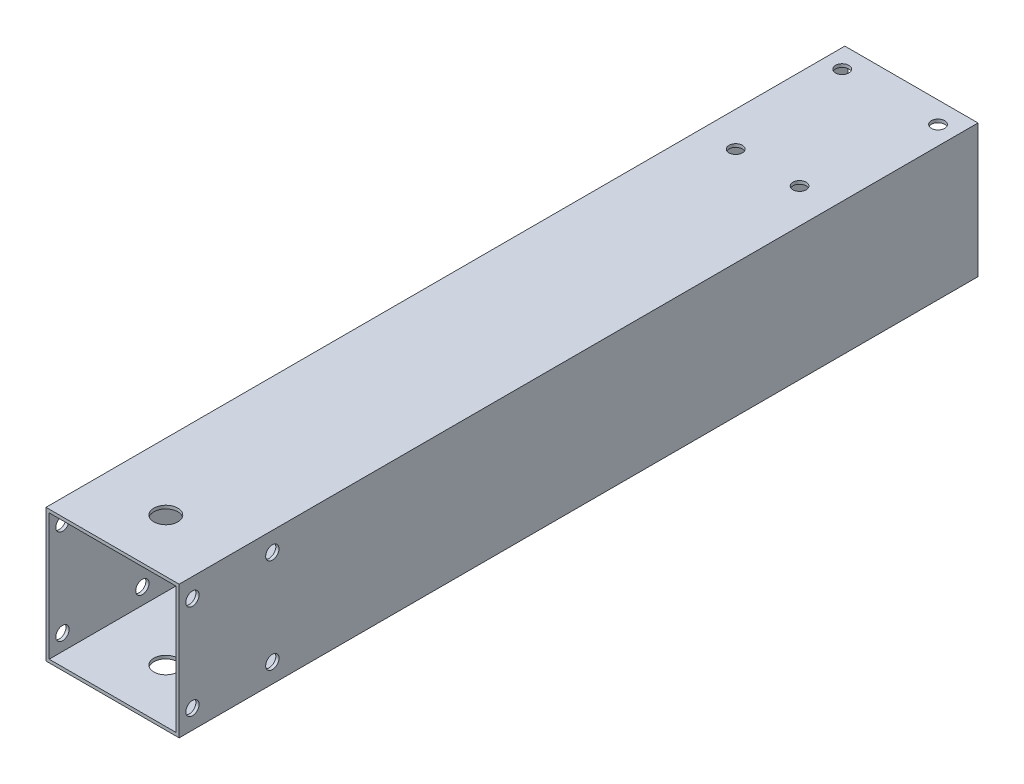
SolidWorks part; units mm, degrees
ref_plane "Alzado" through (0, 0, 0) normal (0, 0, 1) x (1, 0, 0)
ref_plane "Planta" through (0, 0, 0) normal (0, 1, 0) x (1, 0, 0)
ref_plane "Vista lateral" through (0, 0, 0) normal (1, 0, 0) x (0, 0, -1)
sketch "Croquis1" plane through (0, 0, 0) normal (0, 0, 1) x (1, 0, 0)
  line L0 (-23.8, 23.8) -> (-23.8, -23.8)
  line L1 (-25, 25) -> (25, 25)
  line L2 (-25, 25) -> (-25, -25)
  line L3 (-25, -25) -> (25, -25)
  line L4 (25, 25) -> (25, -25)
  line L5 (-25, 25) -> (25, -25) construction
  line L6 (-25, -25) -> (25, 25) construction
  line L7 (-23.8, -23.8) -> (23.8, -23.8)
  line L8 (23.8, 23.8) -> (23.8, -23.8)
  line L9 (-23.8, 23.8) -> (23.8, 23.8)
  point P0 (0, 0)
  dimension "D1" = 50
  dimension "D2" = 50
  dimension "D3" = 1.2
extrude "Saliente-Extruir1" add sketch "Croquis1" along normal blind 300
sketch "Croquis2" plane through (25, 0, 0) normal (1, 0, 0) x (0, 0, -1)
  line L0 (0, -25) -> (0, 25) construction
  line L1 (-300, 25) -> (0, 25) construction
  line L2 (-300, -25) -> (0, -25) construction
  line L7 (0, 17.8) -> (-300, 17.8) construction
  line L8 (-300, -25) -> (-300, 25) construction
  line L9 (0, -17.8) -> (-300, -17.8) construction
  line L10 (-295, 25) -> (-295, -25) construction
  line L11 (-265, 25) -> (-265, -25) construction
  line L12 (-300, 0) -> (-283, 0) construction
  circle A4 centre (-295, 17.8) radius 2.5
  circle A5 centre (-265, 17.8) radius 2.5
  circle A6 centre (-265, -17.8) radius 2.5
  circle A7 centre (-295, -17.8) radius 2.5
  dimension "D11" = 5
  dimension "D12" = 5
  dimension "D13" = 5
  dimension "D14" = 5
  dimension "D2" = 7.2
  dimension "D3" = 7.2
  dimension "D9" = 5
  dimension "D10" = 30
  dimension "D15" = 17
extrude "Cortar-Extruir1" cut sketch "Croquis2" against normal through all
sketch "Croquis3" plane through (0, 25, 0) normal (0, 1, 0) x (1, 0, 0)
  line L0 (0, 0) -> (0, -300) construction
  line L2 (25, -300) -> (-25, -300) construction
  line L3 (25, 0) -> (-25, 0) construction
  circle A0 centre (0, -280) radius 4.5
  dimension "D1" = 9
  dimension "D2" = 20
extrude "Cortar-Extruir2" cut sketch "Croquis3" against normal through all
sketch "Croquis4" plane through (0, -25, 0) normal (0, -1, 0) x (1, 0, 0)
  line L0 (0, 0) -> (0, 30) construction
  line L1 (-25, 0) -> (25, 0) construction
  circle A0 centre (0, 30) radius 8
  dimension "D2" = 16
  dimension "D1" = 30
extrude "Cortar-Extruir3" cut sketch "Croquis4" against normal blind 2
sketch "Croquis5" plane through (0, -25, 0) normal (0, -1, 0) x (1, 0, 0)
  line L0 (-25, 0) -> (25, 0) construction
  line L3 (0, 30) -> (0, 0) construction
  circle A0 centre (-18, 8) radius 2.5
  circle A1 centre (-12, 54) radius 2.5
  circle A2 centre (0, 30) radius 8 construction
  circle A3 centre (18, 8) radius 2.5
  circle A4 centre (12, 54) radius 2.5
  point P4 (0, 0)
  dimension "D1" = 5
  dimension "D2" = 5
  dimension "D3" = 18
  dimension "D4" = 8
  dimension "D5" = 24
  dimension "D6" = 12
extrude "Cortar-Extruir4" cut sketch "Croquis5" against normal through all
